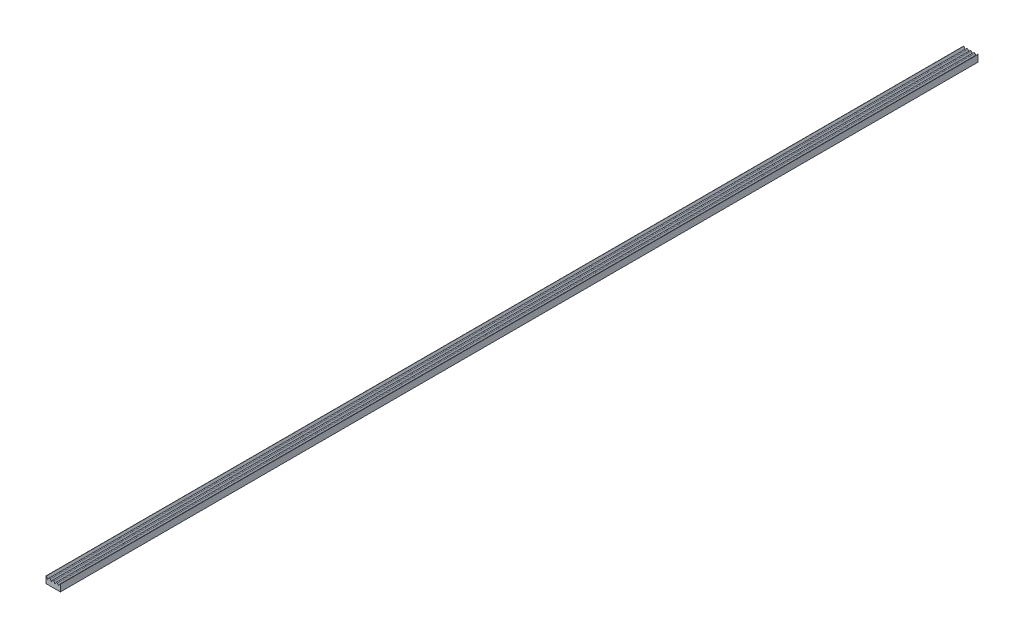
SolidWorks part; units mm, degrees
material "Polyurethane Foam Flexible"
ref_plane "Front Plane" through (0, 0, 0) normal (0, 0, 1) x (1, 0, 0)
ref_plane "Top Plane" through (0, 0, 0) normal (0, 1, 0) x (1, 0, 0)
ref_plane "Right Plane" through (0, 0, 0) normal (1, 0, 0) x (0, 0, -1)
sketch "Sketch1" plane through (0, 0, 0) normal (0, 0, 1) x (1, 0, 0)
  line L0 (-12.7, 6.35) -> (0, 6.35) construction
  line L1 (0, 0) -> (-12.7, 0)
  line L2 (0, 0) -> (0, 5.9072)
  line L3 (-6.35, 0) -> (-6.35, 6.35) construction
  line L4 (-12.7, 0) -> (-12.7, 5.9072)
  line L5 (-12.7, 3.81) -> (0, 3.81) construction
  line L6 (-7.9375, 3.81) -> (-6.8885, 5.4884)
  line L7 (-7.9375, 3.81) -> (-8.9865, 5.4884)
  line L8 (-10.0635, 5.4884) -> (-11.1125, 3.81)
  line L9 (-11.1125, 3.81) -> (-12.4653, 5.9745)
  line L10 (-4.7625, 3.81) -> (-5.8115, 5.4884)
  line L11 (-4.7625, 3.81) -> (-3.7135, 5.4884)
  line L14 (-2.6365, 5.4884) -> (-1.5875, 3.81)
  line L15 (-1.5875, 3.81) -> (-0.2347, 5.9745)
  arc A0 (-3.7135, 5.4884) -> (-2.6365, 5.4884) centre (-3.175, 5.1519) cw
  arc A1 (-6.8885, 5.4884) -> (-5.8115, 5.4884) centre (-6.35, 5.1519) cw
  arc A2 (-8.9865, 5.4884) -> (-10.0635, 5.4884) centre (-9.525, 5.1519) ccw
  arc A3 (0, 5.9072) -> (-0.2347, 5.9745) centre (-0.127, 5.9072) ccw
  arc A4 (-12.4653, 5.9745) -> (-12.7, 5.9072) centre (-12.573, 5.9072) ccw
  dimension "D7" = 0.635
  dimension "D8" = 0.127
  dimension "D1" = 6.35
  dimension "D2" = 12.7
  dimension "D3" = 1.5875
  dimension "D4" = 2.54
  dimension "D5" = 1.5875
extrude "Boss-Extrude1" add sketch "Sketch1" along normal blind 809.625
